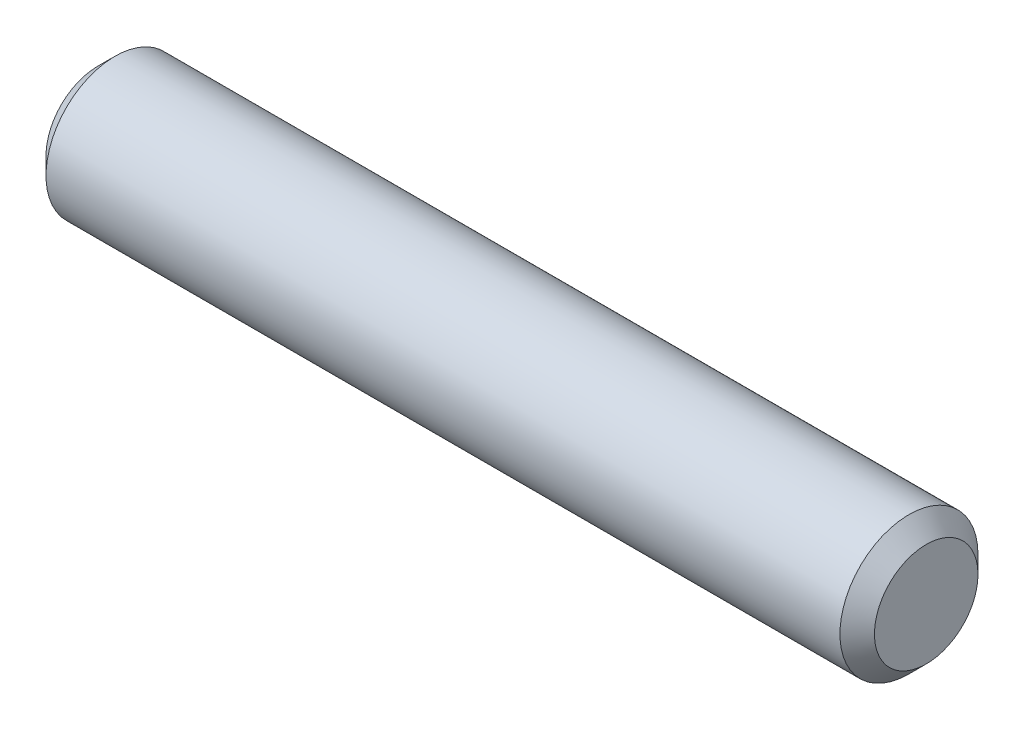
SolidWorks part; units mm, degrees
ref_plane "Plan de face" through (0, 0, 0) normal (0, 0, 1) x (1, 0, 0)
ref_plane "Plan de dessus" through (0, 0, 0) normal (0, 1, 0) x (1, 0, 0)
ref_plane "Plan de droite" through (0, 0, 0) normal (1, 0, 0) x (0, 0, -1)
sketch "Esquisse1" plane through (0, 0, 0) normal (1, 0, 0) x (0, 0, -1)
  circle A0 centre (0, 0) radius 2
  dimension "D1" = 4
extrude "Boss.-Extru.1" add sketch "Esquisse1" along normal mid plane 24
chamfer "Chanfrein1" distance 0.5 angle 45 2 edges at (-12, 0, -2) (12, 0, -2)
